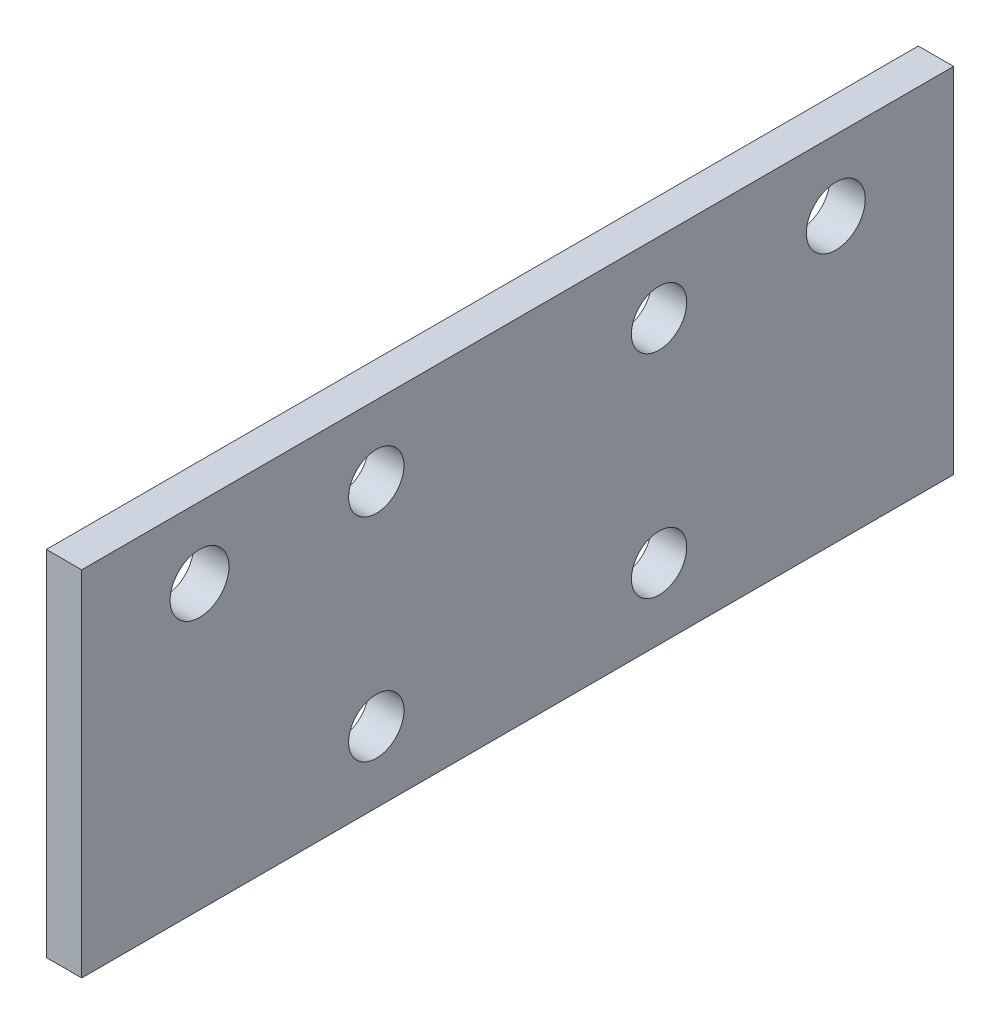
SolidWorks part; units mm, degrees
ref_plane "Front Plane" through (0, 0, 0) normal (0, 0, 1) x (1, 0, 0)
ref_plane "Top Plane" through (0, 0, 0) normal (0, 1, 0) x (1, 0, 0)
ref_plane "Right Plane" through (0, 0, 0) normal (1, 0, 0) x (0, 0, -1)
sketch "Sketch1" plane through (0, 0, 0) normal (1, 0, 0) x (0, 0, -1)
  line L0 (-26.5663, -17.1888) -> (13.4337, -17.1888)
  line L1 (13.4337, -17.1888) -> (13.4337, 12.8112)
  line L2 (13.4337, 12.8112) -> (-26.5663, 12.8112)
  line L3 (-26.5663, 12.8112) -> (-26.5663, -17.1888)
  line L4 (-43.5663, -17.1888) -> (-26.5663, -17.1888)
  line L5 (-26.5663, -17.1888) -> (-26.5663, 12.8112)
  line L6 (-26.5663, 12.8112) -> (-43.5663, 12.8112)
  line L7 (-43.5663, 12.8112) -> (-43.5663, -17.1888)
  line L8 (13.4337, -17.1888) -> (30.4337, -17.1888)
  line L9 (30.4337, -17.1888) -> (30.4337, 12.8112)
  line L10 (30.4337, 12.8112) -> (13.4337, 12.8112)
  line L11 (13.4337, 12.8112) -> (13.4337, -17.1888)
  circle A0 centre (-18.5663, -11.1888) radius 2.35
  circle A1 centre (5.4337, -11.1888) radius 2.35
  circle A2 centre (5.4337, 6.8112) radius 2.35
  circle A3 centre (-18.5663, 6.8112) radius 2.35
  circle A4 centre (20.4337, 6.8112) radius 2.5
  circle A5 centre (-33.5663, 6.8112) radius 2.5
extrude "Boss-Extrude1" add sketch "Sketch1" along normal blind 3 contours L9 L10 L1 L8 A4 | L2 L3 L0 L1 A3 A2 A1 A0 | L6 L7 L4 L3 A5
